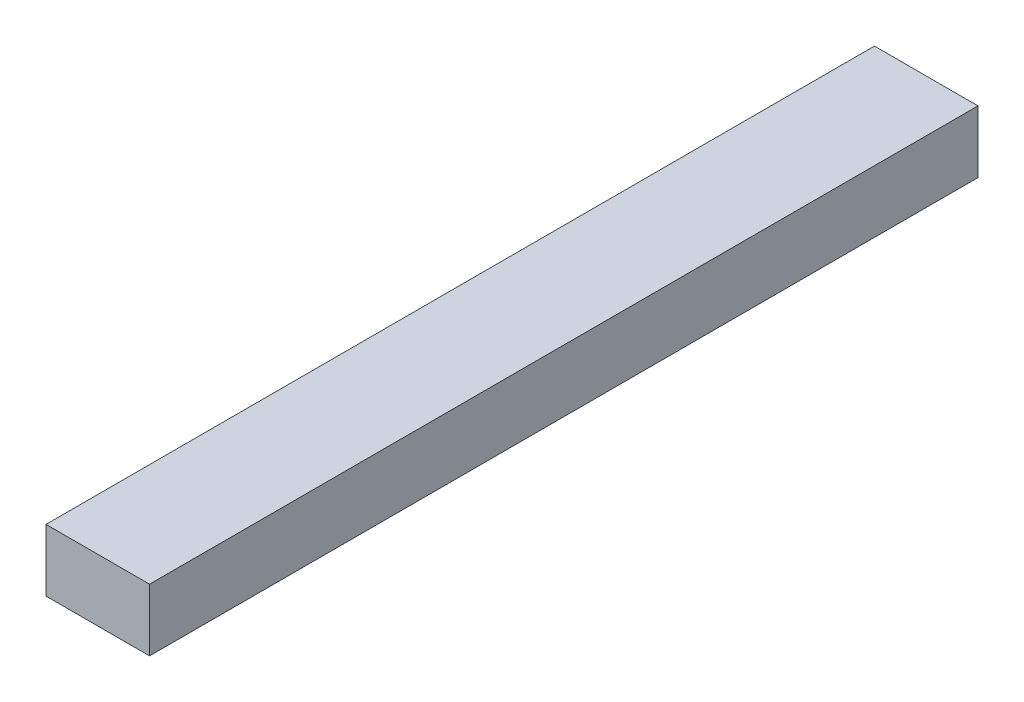
SolidWorks part; units mm, degrees
material "Kiefer"
ref_plane "Ebene vorne" through (0, 0, 0) normal (0, 0, 1) x (1, 0, 0)
ref_plane "Ebene oben" through (0, 0, 0) normal (0, 1, 0) x (1, 0, 0)
ref_plane "Ebene rechts" through (0, 0, 0) normal (1, 0, 0) x (0, 0, -1)
sketch "Skizze1" plane through (0, 0, 0) normal (0, 0, 1) x (1, 0, 0)
  line L0 (0, 0) -> (0, 40.512) construction
  line L2 (50, 30) -> (-50, 30)
  line L3 (50, 30) -> (50, -30)
  line L4 (50, -30) -> (-50, -30)
  line L5 (-50, 30) -> (-50, -30)
  line L6 (50, 30) -> (-50, -30) construction
  line L7 (50, -30) -> (-50, 30) construction
  dimension "D1" = 100
  dimension "D2" = 60
extrude "Aufsatz-Linear austragen1" add sketch "Skizze1" along normal blind 800
